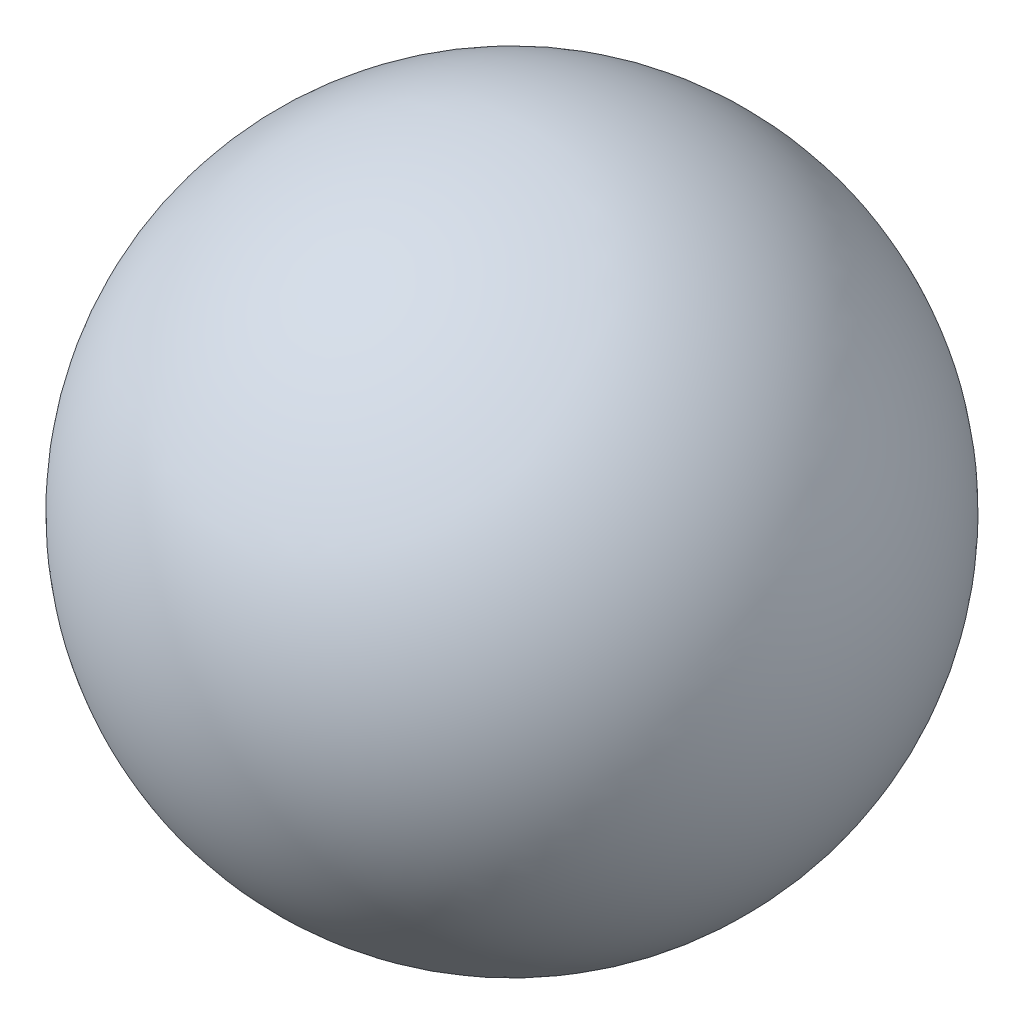
SolidWorks part; units mm, degrees
ref_plane "前视基准面" through (0, 0, 0) normal (0, 0, 1) x (1, 0, 0)
ref_plane "上视基准面" through (0, 0, 0) normal (0, 1, 0) x (1, 0, 0)
ref_plane "右视基准面" through (0, 0, 0) normal (1, 0, 0) x (0, 0, -1)
sketch "Sketch1" plane through (0, 0, 0) normal (0, 1, 0) x (1, 0, 0)
  line L0 (0, 9.9) -> (0, -9.9)
  arc A0 (0, -9.9) -> (0, 9.9) centre (0, 0) cw
  dimension "D1" = 9.9
revolve "Revolve1" add sketch "Sketch1" angle 360 about L0
